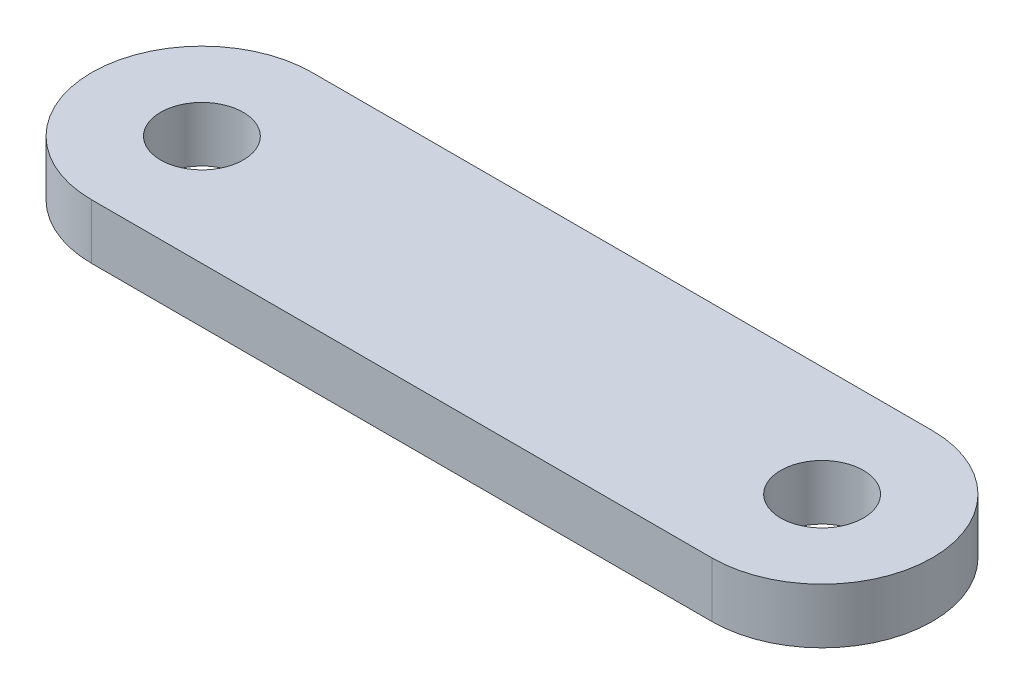
SolidWorks part; units mm, degrees
ref_plane "Front Plane" through (0, 0, 0) normal (0, 0, 1) x (1, 0, 0)
ref_plane "Top Plane" through (0, 0, 0) normal (0, 1, 0) x (1, 0, 0)
ref_plane "Right Plane" through (0, 0, 0) normal (1, 0, 0) x (0, 0, -1)
sketch "Sketch1" plane through (0, 0, 0) normal (0, 1, 0) x (1, 0, 0)
  line L0 (-14.2875, 0) -> (14.2875, 0) construction
  line L1 (-14.2875, 5.08) -> (14.2875, 5.08)
  line L2 (-14.2875, -5.08) -> (14.2875, -5.08)
  arc A0 (-14.2875, 5.08) -> (-14.2875, -5.08) centre (-14.2875, 0) ccw
  arc A1 (14.2875, -5.08) -> (14.2875, 5.08) centre (14.2875, 0) ccw
  circle A2 centre (-14.2875, 0) radius 1.905
  circle A3 centre (14.2875, 0) radius 1.905
  point P2 (0, 0)
  dimension "D2" = 3.81
  dimension "D3" = 3.175
  dimension "D1" = 28.575
extrude "Boss-Extrude1" add sketch "Sketch1" along normal blind 2.54
